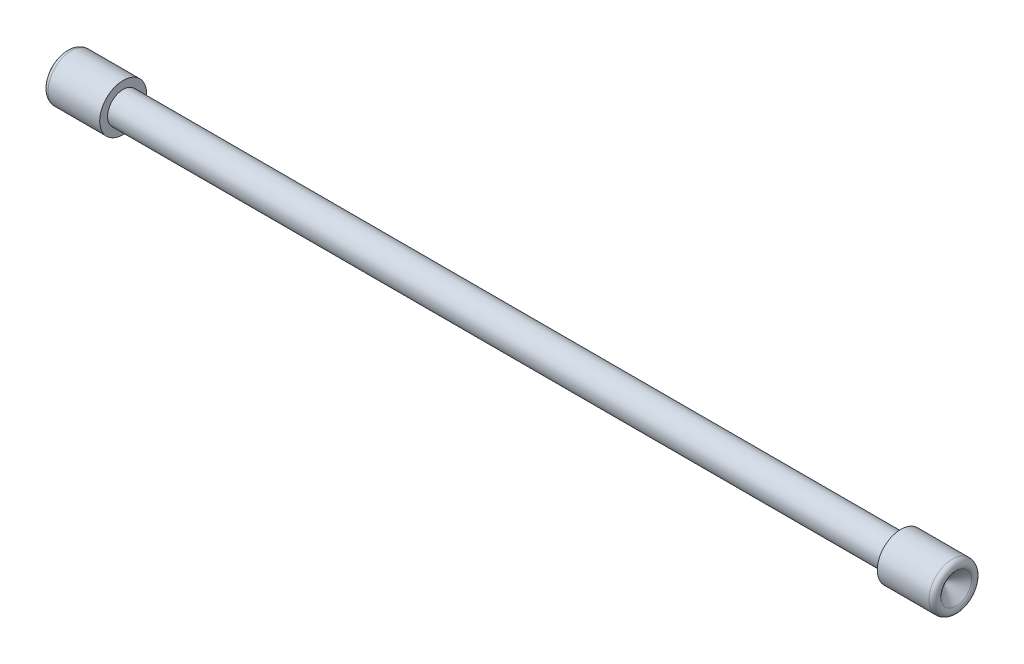
SolidWorks part; units mm, degrees
material "Delrin 2700 NC010, Low Viscosity Acetal Copolymer (SS)"
ref_plane "Front Plane" through (0, 0, 0) normal (0, 0, 1) x (1, 0, 0)
ref_plane "Top Plane" through (0, 0, 0) normal (0, 1, 0) x (1, 0, 0)
ref_plane "Right Plane" through (0, 0, 0) normal (1, 0, 0) x (0, 0, -1)
sketch "Sketch1" plane through (0, 0, 0) normal (0, 0, 1) x (1, 0, 0)
  line L0 (144, 7.5) -> (137.2918, 0)
  line L1 (0, 0) -> (124, 0)
  line L2 (0, 0) -> (0, 5)
  line L3 (0, 5) -> (124, 5)
  line L5 (124, 0) -> (144, 0)
  line L6 (124, 5) -> (124, 7.5)
  line L7 (124, 7.5) -> (144, 7.5)
  line L8 (144, 0) -> (144, 7.5)
  circle A0 centre (144, 0) radius 5 construction
  arc A1 (141.6459, 4.868) -> (140.4688, 7.5) centre (140.4688, 5.9208) ccw
  point P9 (-144, 0)
  point P15 (140.6459, 3.75)
  dimension "D6" = 10
  dimension "D7" = 1.5
  dimension "D1" = 5
  dimension "D2" = 7.5
  dimension "D3" = 144
  dimension "D4" = 20
  dimension "D5" = 288
revolve "Revolve1" add sketch "Sketch1" angle 360 about L1
mirror "Mirror1" about plane through (0, 0, 0) normal (-1, 0, 0) of "Revolve1"
